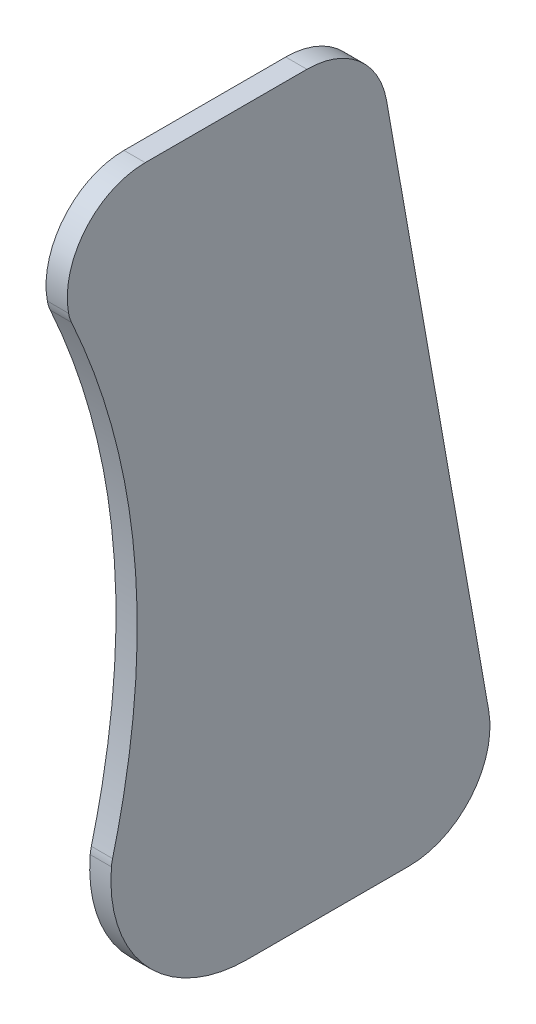
SolidWorks part; units mm, degrees
material "ABS"
ref_plane "Front Plane" through (0, 0, 0) normal (0, 0, 1) x (1, 0, 0)
ref_plane "Top Plane" through (0, 0, 0) normal (0, 1, 0) x (1, 0, 0)
ref_plane "Right Plane" through (0, 0, 0) normal (1, 0, 0) x (0, 0, -1)
sketch "Sketch1" plane through (0, 0, 0) normal (1, 0, 0) x (0, 0, -1)
  line L0 (-0.8588, 31.1045) -> (29.6212, 31.1045)
  line L1 (44.6297, 48.9909) -> (25.3712, 158.2109)
  line L2 (10.3628, 170.8045) -> (-20.1172, 170.8045)
  arc A0 (29.6212, 31.1045) -> (44.6297, 48.9909) centre (29.6212, 46.3445) ccw
  arc A1 (25.3712, 158.2109) -> (10.3628, 170.8045) centre (10.3628, 155.5645) ccw
  arc A2 (-0.8588, 31.1045) -> (-26.4164, 59.73) centre (-0.8588, 56.8265) cw
  arc A3 (-20.1172, 170.8045) -> (-34.3191, 152.3494) centre (-20.1172, 156.1126) ccw
  spline S0 degree 2 poles (-34.3191, 152.3494) (-13.8259, 107.793) (-26.4164, 59.73) knots 0 0 0 1 1 1
  point P6 (47.7835, 31.1045)
  point P9 (-41.9725, 144.1653)
  point P15 (-43.5811, 29.6195)
  point P16 (0, 0)
  point P17 (0, 0)
  point P18 (-30.8268, 53.5822)
  point P19 (-39.3374, 142.9889)
  point P20 (-18.8298, 97.3468)
  point P21 (-26.4164, 59.73)
  point P22 (-34.3191, 152.3494)
  point P23 (-22.6572, 112.2038)
  dimension "D4" = 15.24
  dimension "D5" = 139.7
  dimension "D1" = 30.48
  dimension "D2" = 80
  dimension "D3" = 30.48
extrude "Boss-Extrude1" add sketch "Sketch1" along normal blind 4
fillet "Fillet1" radius 7.62 1 edges at (2, 152.3494, 34.3191)
fillet "Fillet2" radius 7.62 1 edges at (2, 59.73, 26.4164)
